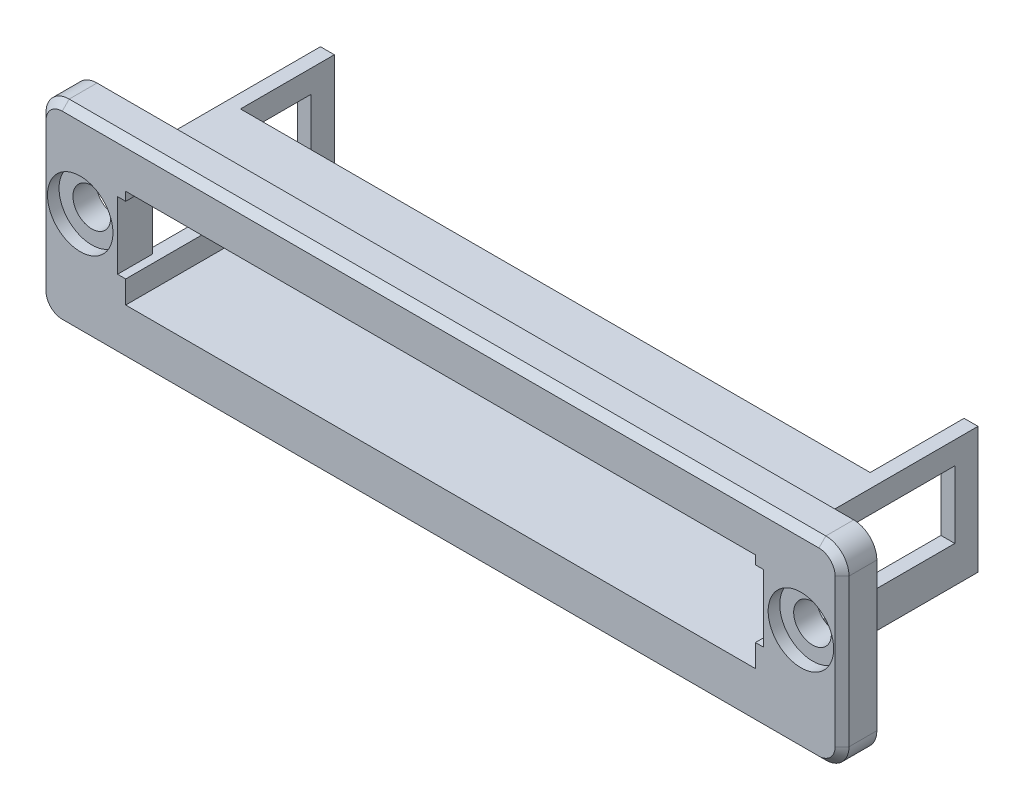
SolidWorks part; units mm, degrees
material "Nylon 101"
ref_plane "Front Plane" through (0, 0, 0) normal (0, 0, 1) x (1, 0, 0)
ref_plane "Top Plane" through (0, 0, 0) normal (0, 1, 0) x (1, 0, 0)
ref_plane "Right Plane" through (0, 0, 0) normal (1, 0, 0) x (0, 0, -1)
sketch "SK Flange" plane through (0, 0, 0) normal (0, 0, 1) x (1, 0, 0)
  line L0 (-32.635, -9.25) -> (32.635, -9.25)
  line L1 (34.635, -7.25) -> (34.635, 5.5)
  line L2 (32.635, 7.5) -> (-32.635, 7.5)
  line L3 (-34.635, 5.5) -> (-34.635, -7.25)
  arc A0 (32.635, -9.25) -> (34.635, -7.25) centre (32.635, -7.25) ccw
  arc A1 (34.635, 5.5) -> (32.635, 7.5) centre (32.635, 5.5) ccw
  arc A2 (-32.635, 7.5) -> (-34.635, 5.5) centre (-32.635, 5.5) ccw
  arc A3 (-34.635, -7.25) -> (-32.635, -9.25) centre (-32.635, -7.25) ccw
extrude "Flange" add sketch "SK Flange" along normal blind 3
chamfer "Front bevel" distance 0.6 angle 45 8 edges at (-34.635, -0.875, 3) (-34.0492, 6.9142, 3) (0, 7.5, 3) (34.0492, 6.9142, 3) (34.635, -0.875, 3) (34.0492, -8.6642, 3) (0, -9.25, 3) (-34.0492, -8.6642, 3)
sketch "SK Opening" plane through (0, 0, 0) normal (0, 0, 1) x (1, 0, 0)
  line L0 (-27.16, -4.85) -> (27.16, -4.85)
  line L1 (27.16, -4.85) -> (27.16, -2.9)
  line L2 (27.16, -2.9) -> (27.86, -2.9)
  line L3 (27.86, -2.9) -> (27.86, 2.9)
  line L4 (27.86, 2.9) -> (27.16, 2.9)
  line L5 (27.16, 2.9) -> (27.16, 3.65)
  line L6 (27.16, 3.65) -> (-27.16, 3.65)
  line L7 (-27.16, 3.65) -> (-27.16, 2.9)
  line L8 (-27.16, 2.9) -> (-27.86, 2.9)
  line L9 (-27.86, 2.9) -> (-27.86, -2.9)
  line L10 (-27.86, -2.9) -> (-27.16, -2.9)
  line L11 (-27.16, -2.9) -> (-27.16, -4.85)
  circle A0 centre (-31.085, 0) radius 1.625
  circle A1 centre (31.085, 0) radius 1.625
extrude "Opening + holes" cut sketch "SK Opening" against normal through all and the other way through all
ref_plane "PL front face" through (0, 0, 3) normal (0, 0, 1) x (1, 0, 0)
sketch "SK Counterbore" plane through (0, 0, 3) normal (0, 0, 1) x (1, 0, 0)
  circle A0 centre (-31.085, 0) radius 2.825
  circle A1 centre (31.085, 0) radius 2.825
extrude "Counterbore" cut sketch "SK Counterbore" against normal blind 1
sketch "SK Long walls" plane through (0, 0, 0) normal (0, 0, 1) x (1, 0, 0)
  line L0 (-28.36, 3.65) -> (28.36, 3.65)
  line L1 (28.36, 3.65) -> (28.36, 4.85)
  line L2 (28.36, 4.85) -> (-28.36, 4.85)
  line L3 (-28.36, 4.85) -> (-28.36, 3.65)
  line L4 (-28.36, -6.05) -> (28.36, -6.05)
  line L5 (28.36, -6.05) -> (28.36, -4.85)
  line L6 (28.36, -4.85) -> (-28.36, -4.85)
  line L7 (-28.36, -4.85) -> (-28.36, -6.05)
extrude "Long walls" add sketch "SK Long walls" against normal blind 6.9
sketch "SK Legs" plane through (0, 0, 0) normal (0, 0, 1) x (1, 0, 0)
  line L0 (-27.16, 2.9) -> (-28.36, 2.9)
  line L1 (-28.36, 2.9) -> (-28.36, 4.85)
  line L2 (-28.36, 4.85) -> (-27.16, 4.85)
  line L3 (-27.16, 4.85) -> (-27.16, 2.9)
  line L4 (-27.16, -6.05) -> (-28.36, -6.05)
  line L5 (-28.36, -6.05) -> (-28.36, -2.9)
  line L6 (-28.36, -2.9) -> (-27.16, -2.9)
  line L7 (-27.16, -2.9) -> (-27.16, -6.05)
  line L8 (27.16, 2.9) -> (28.36, 2.9)
  line L9 (28.36, 2.9) -> (28.36, 4.85)
  line L10 (28.36, 4.85) -> (27.16, 4.85)
  line L11 (27.16, 4.85) -> (27.16, 2.9)
  line L12 (27.16, -6.05) -> (28.36, -6.05)
  line L13 (28.36, -6.05) -> (28.36, -2.9)
  line L14 (28.36, -2.9) -> (27.16, -2.9)
  line L15 (27.16, -2.9) -> (27.16, -6.05)
extrude "Legs" add sketch "SK Legs" against normal blind 13
ref_plane "PL leg tips" through (0, 0, -13) normal (0, 0, 1) x (1, 0, 0)
sketch "SK Leg ties" plane through (0, 0, -13) normal (0, 0, 1) x (1, 0, 0)
  line L0 (-27.16, -6.05) -> (-28.36, -6.05)
  line L1 (-28.36, -6.05) -> (-28.36, 4.85)
  line L2 (-28.36, 4.85) -> (-27.16, 4.85)
  line L3 (-27.16, 4.85) -> (-27.16, -6.05)
  line L4 (27.16, -6.05) -> (28.36, -6.05)
  line L5 (28.36, -6.05) -> (28.36, 4.85)
  line L6 (28.36, 4.85) -> (27.16, 4.85)
  line L7 (27.16, 4.85) -> (27.16, -6.05)
extrude "Leg ties" add sketch "SK Leg ties" against normal blind 2
